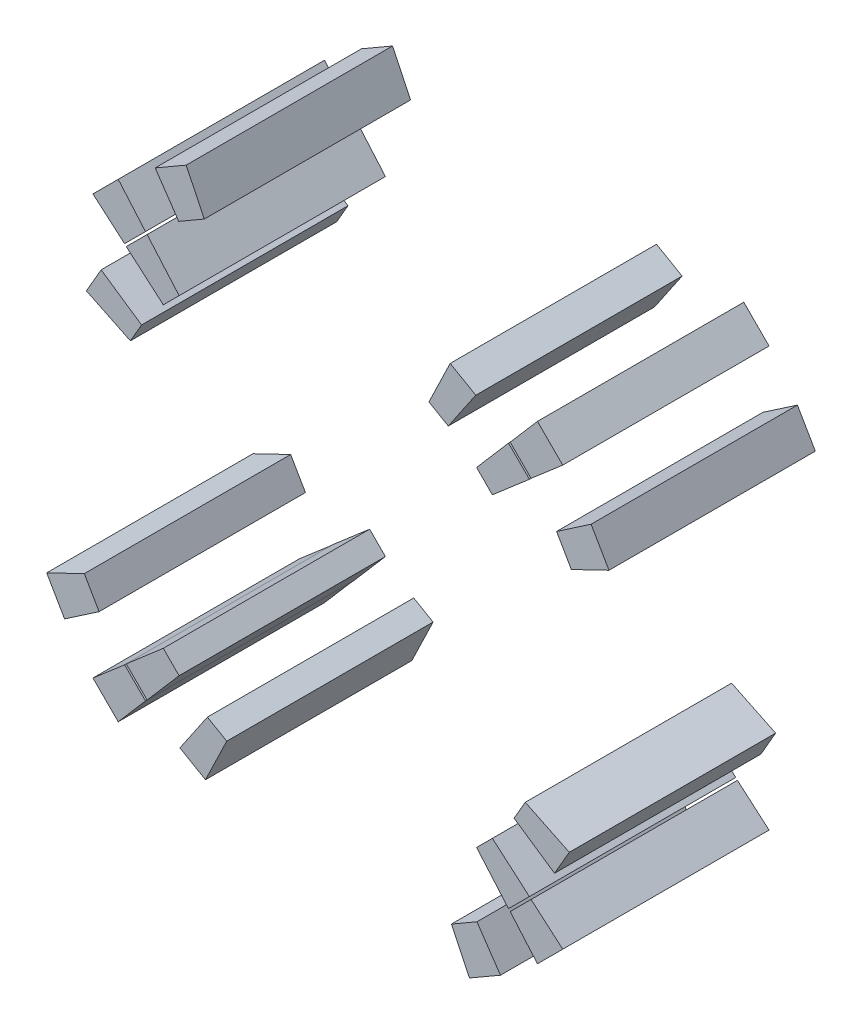
SolidWorks part; units mm, degrees
ref_plane "Спереди" through (0, 0, 0) normal (0, 0, 1) x (1, 0, 0)
ref_plane "Сверху" through (0, 0, 0) normal (0, 1, 0) x (1, 0, 0)
ref_plane "Справа" through (0, 0, 0) normal (1, 0, 0) x (0, 0, -1)
sketch "Эскиз1" plane through (0, 0, 0) normal (0, 0, 1) x (1, 0, 0)
  line L0 (35.4045, 17.9613) -> (40.8774, 20.5983)
  line L1 (40.8774, 20.5983) -> (38.2774, 25.1017)
  line L2 (38.2774, 25.1017) -> (33.2572, 21.6806)
  line L3 (33.2572, 21.6806) -> (35.4045, 17.9613)
  line L4 (23.9243, 21.6262) -> (29.3077, 26.2709)
  line L5 (29.3077, 26.2709) -> (26.2709, 29.3077)
  line L6 (26.2709, 29.3077) -> (21.6262, 23.9243)
  line L7 (21.6262, 23.9243) -> (23.9243, 21.6262)
  line L8 (29.5494, 26.5127) -> (34.1533, 30.4763)
  line L9 (34.1533, 30.4763) -> (30.4763, 34.1533)
  line L10 (30.4763, 34.1533) -> (26.5127, 29.5494)
  line L11 (26.5127, 29.5494) -> (29.5494, 26.5127)
  line L12 (17.5118, 27.0813) -> (21.5096, 32.9611)
  line L13 (21.5096, 32.9611) -> (17.7904, 35.1085)
  line L14 (17.7904, 35.1085) -> (14.6972, 28.7063)
  line L15 (14.6972, 28.7063) -> (17.5118, 27.0813)
  line L16 (-17.9613, 35.4045) -> (-20.5983, 40.8774)
  line L17 (-20.5983, 40.8774) -> (-25.1017, 38.2774)
  line L18 (-25.1017, 38.2774) -> (-21.6806, 33.2572)
  line L19 (-21.6806, 33.2572) -> (-17.9613, 35.4045)
  line L20 (-21.6262, 23.9243) -> (-26.2709, 29.3077)
  line L21 (-26.2709, 29.3077) -> (-29.3077, 26.2709)
  line L22 (-29.3077, 26.2709) -> (-23.9243, 21.6262)
  line L23 (-23.9243, 21.6262) -> (-21.6262, 23.9243)
  line L24 (-26.5127, 29.5494) -> (-30.4763, 34.1533)
  line L25 (-30.4763, 34.1533) -> (-34.1533, 30.4763)
  line L26 (-34.1533, 30.4763) -> (-29.5494, 26.5127)
  line L27 (-29.5494, 26.5127) -> (-26.5127, 29.5494)
  line L28 (-27.0813, 17.5118) -> (-32.9611, 21.5096)
  line L29 (-32.9611, 21.5096) -> (-35.1085, 17.7904)
  line L30 (-35.1085, 17.7904) -> (-28.7063, 14.6972)
  line L31 (-28.7063, 14.6972) -> (-27.0813, 17.5118)
  line L32 (-35.4045, -17.9613) -> (-40.8774, -20.5983)
  line L33 (-40.8774, -20.5983) -> (-38.2774, -25.1017)
  line L34 (-38.2774, -25.1017) -> (-33.2572, -21.6806)
  line L35 (-33.2572, -21.6806) -> (-35.4045, -17.9613)
  line L36 (-23.9243, -21.6262) -> (-29.3077, -26.2709)
  line L37 (-29.3077, -26.2709) -> (-26.2709, -29.3077)
  line L38 (-26.2709, -29.3077) -> (-21.6262, -23.9243)
  line L39 (-21.6262, -23.9243) -> (-23.9243, -21.6262)
  line L40 (-29.5494, -26.5127) -> (-34.1533, -30.4763)
  line L41 (-34.1533, -30.4763) -> (-30.4763, -34.1533)
  line L42 (-30.4763, -34.1533) -> (-26.5127, -29.5494)
  line L43 (-26.5127, -29.5494) -> (-29.5494, -26.5127)
  line L44 (-17.5118, -27.0813) -> (-21.5096, -32.9611)
  line L45 (-21.5096, -32.9611) -> (-17.7904, -35.1085)
  line L46 (-17.7904, -35.1085) -> (-14.6972, -28.7063)
  line L47 (-14.6972, -28.7063) -> (-17.5118, -27.0813)
  line L48 (17.9613, -35.4045) -> (20.5983, -40.8774)
  line L49 (20.5983, -40.8774) -> (25.1017, -38.2774)
  line L50 (25.1017, -38.2774) -> (21.6806, -33.2572)
  line L51 (21.6806, -33.2572) -> (17.9613, -35.4045)
  line L52 (21.6262, -23.9243) -> (26.2709, -29.3077)
  line L53 (26.2709, -29.3077) -> (29.3077, -26.2709)
  line L54 (29.3077, -26.2709) -> (23.9243, -21.6262)
  line L55 (23.9243, -21.6262) -> (21.6262, -23.9243)
  line L56 (26.5127, -29.5494) -> (30.4763, -34.1533)
  line L57 (30.4763, -34.1533) -> (34.1533, -30.4763)
  line L58 (34.1533, -30.4763) -> (29.5494, -26.5127)
  line L59 (29.5494, -26.5127) -> (26.5127, -29.5494)
  line L60 (27.0813, -17.5118) -> (32.9611, -21.5096)
  line L61 (32.9611, -21.5096) -> (35.1085, -17.7904)
  line L62 (35.1085, -17.7904) -> (28.7063, -14.6972)
  line L63 (28.7063, -14.6972) -> (27.0813, -17.5118)
extrude "Coil_sides" add sketch "Эскиз1" along normal blind 30 from offset 15 separate body
